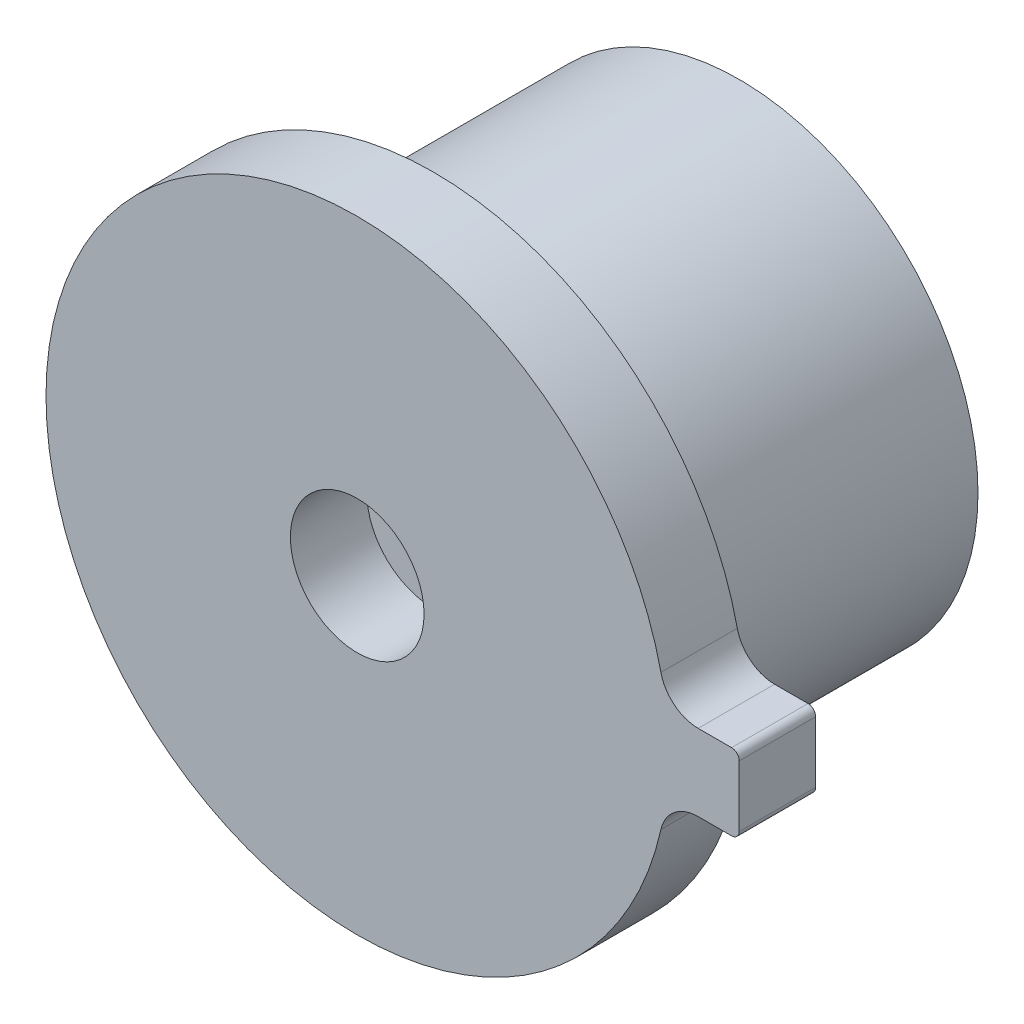
SolidWorks part; units mm, degrees
material "ABS"
ref_plane "Plan de face" through (0, 0, 0) normal (0, 0, 1) x (1, 0, 0)
ref_plane "Plan de dessus" through (0, 0, 0) normal (0, 1, 0) x (1, 0, 0)
ref_plane "Plan de droite" through (0, 0, 0) normal (1, 0, 0) x (0, 0, -1)
sketch "Esquisse1" plane through (0, 0, 0) normal (0, 0, 1) x (1, 0, 0)
  circle A0 centre (0, 0) radius 12.5
  circle A1 centre (0, 0) radius 2
  dimension "D1" = 25
  dimension "D2" = 4
extrude "Boss.-Extru.1" add sketch "Esquisse1" along normal blind 16
sketch "Esquisse2" plane through (0, 0, 16) normal (0, 0, 1) x (1, 0, 0)
  circle A0 centre (0, 0) radius 16.2932
  circle A1 centre (0, 0) radius 2 construction
  circle A2 centre (0, 0) radius 2
extrude "Boss.-Extru.2" add sketch "Esquisse2" along normal blind 4
sketch "Esquisse3" plane through (0, 0, 20) normal (0, 0, 1) x (1, 0, 0)
  circle A0 centre (0, 0) radius 3.5
  dimension "D1" = 7
extrude "Enlèv. mat.-Extru.1" cut sketch "Esquisse3" against normal blind 4
sketch "Esquisse4" plane through (0, 0, 20) normal (0, 0, 1) x (1, 0, 0)
  line L0 (0, 0) -> (16.2932, 0) construction
  line L2 (20, 2) -> (12.5864, 2)
  line L3 (20, 2) -> (20, -2)
  line L4 (20, -2) -> (12.5864, -2)
  line L5 (12.5864, 2) -> (12.5864, -2)
  line L6 (20, 2) -> (12.5864, -2) construction
  line L7 (20, -2) -> (12.5864, 2) construction
  circle A0 centre (0, 0) radius 16.2932 construction
  point P8 (0, 0)
  point P10 (16.2932, 0)
  dimension "D1" = 20
  dimension "D2" = 4
extrude "Boss.-Extru.3" add sketch "Esquisse4" against normal blind 4
fillet "Congé1" radius 2 2 edges at (16.17, -2, 18) (16.17, 2, 18)
fillet "Congé2" radius 0.4 2 edges at (20, -2, 18) (20, 2, 18)
sketch "Esquisse5" plane through (0, 0, 0) normal (0, 0, -1) x (-1, 0, 0)
  circle A0 centre (0, 0) radius 6 construction
  circle A1 centre (-6, 0) radius 2.75
  circle A2 centre (3, 5.1962) radius 2.75
  circle A3 centre (3, -5.1962) radius 2.75
  circle A5 centre (0, 0) radius 12.5 construction
  dimension "D1" = 5.5
  dimension "D3" = 12
  dimension "D2" = 3
extrude "Enlèv. mat.-Extru.2" cut sketch "Esquisse5" against normal blind 5
